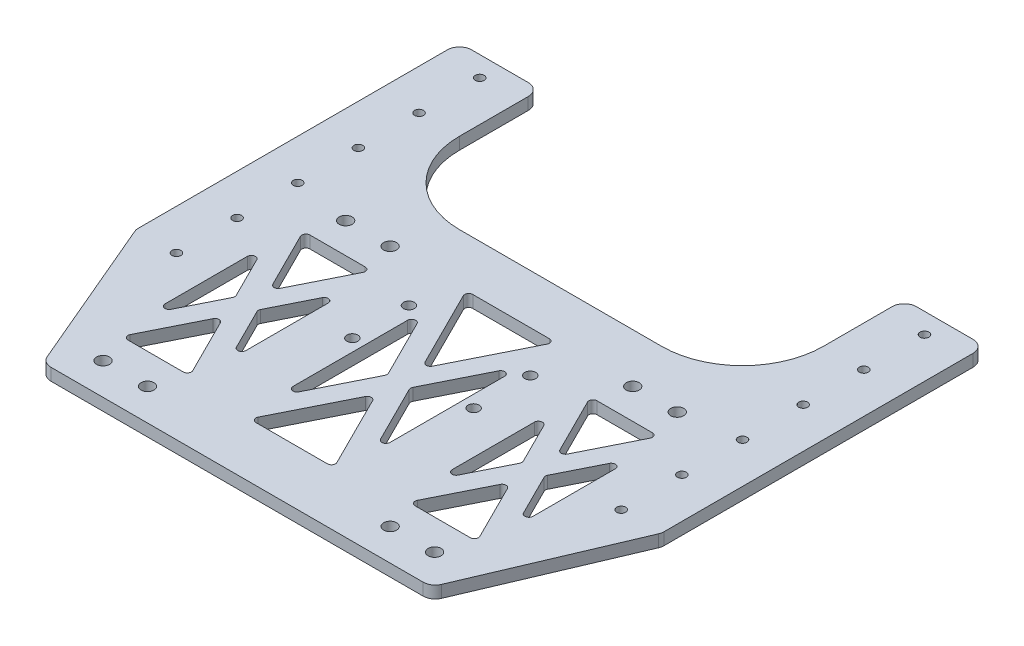
SolidWorks part; units mm, degrees
material "碳纤维"
ref_plane "前视基准面" through (0, 0, 0) normal (0, 0, 1) x (1, 0, 0)
ref_plane "上视基准面" through (0, 0, 0) normal (0, 1, 0) x (1, 0, 0)
ref_plane "右视基准面" through (0, 0, 0) normal (1, 0, 0) x (0, 0, -1)
sketch "草图1" plane through (0, 0, 0) normal (0, 1, 0) x (1, 0, 0)
  line L0 (20, 120) -> (20, 80)
  line L1 (0, 0) -> (130, 0)
  line L2 (0, 0) -> (0, 120)
  line L3 (0, 120) -> (20, 120)
  line L4 (130, 0) -> (130, 120)
  line L5 (65, 0) -> (65, 85) construction
  line L6 (20, 80) -> (110, 80)
  line L7 (110, 120) -> (110, 80)
  line L8 (110, 120) -> (130, 120)
  line L10 (50, 57.5) -> (50, 43.5) construction
  circle A0 centre (10, 115) radius 1.1
  circle A1 centre (120, 115) radius 1.1
  circle A2 centre (10, 100) radius 1.1
  circle A3 centre (120, 100) radius 1.1
  circle A4 centre (10, 85) radius 1.1
  circle A5 centre (120, 85) radius 1.1
  circle A6 centre (10, 70) radius 1.1
  circle A7 centre (120, 70) radius 1.1
  circle A8 centre (10, 55) radius 1.1
  circle A9 centre (120, 55) radius 1.1
  circle A10 centre (10, 40) radius 1.1
  circle A11 centre (120, 40) radius 1.1
  circle A12 centre (50, 57.5) radius 1.35
  circle A13 centre (50, 43.5) radius 1.35
  circle A14 centre (80, 43.5) radius 1.35
  circle A15 centre (80, 57.5) radius 1.35
  point P11 (65, 80)
  dimension "D5" = 2.2
  dimension "D6" = 5
  dimension "D8" = 15
  dimension "D9" = 43.5
  dimension "D10" = 14
  dimension "D11" = 2.7
  dimension "D12" = 30
  dimension "D13" = 10
  dimension "D1" = 130
  dimension "D2" = 120
  dimension "D3" = 40
  dimension "D4" = 90
  dimension "D7" = 6
extrude "凸台-拉伸1" add sketch "草图1" along normal blind 3
sketch "草图2" plane through (0, 0, 0) normal (0, -1, 0) x (1, 0, 0)
  line L0 (35, -7.85) -> (24, -7.85) construction
  line L1 (35, -67.85) -> (35, -7.85) construction
  line L2 (42, -37.85) -> (17, -37.85) construction
  line L3 (29.5, -7.85) -> (29.5, -37.85) construction
  line L4 (65, -80) -> (65, 0) construction
  line L5 (110, -80) -> (20, -80) construction
  line L6 (0, 0) -> (130, 0) construction
  line L8 (42, -12.85) -> (17, -12.85) construction
  line L9 (42, -12.85) -> (42, -62.85) construction
  line L10 (42, -62.85) -> (17, -62.85) construction
  line L11 (17, -12.85) -> (17, -62.85) construction
  line L15 (50.5, -40) -> (65, -40) construction
  line L16 (50.5, -11) -> (79.5, -11) construction
  line L17 (50.5, -11) -> (50.5, -69) construction
  line L18 (50.5, -69) -> (79.5, -69) construction
  line L19 (79.5, -11) -> (79.5, -69) construction
  line L20 (17, -12.85) -> (29.5, -37.85) construction
  line L21 (42, -12.85) -> (29.5, -37.85) construction
  line L22 (29.5, -12.85) -> (29.5, -7.85) construction
  line L23 (35, -48.85) -> (42, -62.85) construction
  line L24 (29.5, -37.85) -> (42, -62.85) construction
  line L25 (29.5, -37.85) -> (17, -62.85) construction
  line L26 (37.9549, -15.35) -> (29.5, -32.2598)
  line L27 (19.5, -23.4402) -> (26.7049, -37.85)
  line L28 (29.5, -43.4402) -> (21.0451, -60.35)
  line L29 (26.7049, -37.85) -> (19.5, -52.2598)
  line L30 (29.5, -43.4402) -> (37.9549, -60.35)
  line L31 (37.9549, -15.35) -> (21.0451, -15.35)
  line L32 (90.5, -23.4402) -> (97.7049, -37.85)
  line L33 (37.9549, -60.35) -> (21.0451, -60.35)
  line L34 (39.5, -23.4402) -> (39.5, -52.2598)
  line L35 (90.5, -23.4402) -> (90.5, -52.2598)
  line L36 (19.5, -23.4402) -> (19.5, -52.2598)
  line L37 (97.7049, -37.85) -> (90.5, -52.2598)
  line L38 (32.2951, -37.85) -> (39.5, -52.2598)
  line L39 (39.5, -23.4402) -> (32.2951, -37.85)
  line L40 (42, -60.35) -> (17, -60.35) construction
  line L41 (27.2639, -38.968) -> (39.7639, -63.968) construction
  line L42 (21.0451, -15.35) -> (29.5, -32.2598)
  line L43 (100.5, -43.4402) -> (92.0451, -60.35)
  line L44 (44.2361, -13.968) -> (31.7361, -38.968) construction
  line L45 (100.5, -43.4402) -> (108.9549, -60.35)
  line L46 (14.7639, -13.968) -> (27.2639, -38.968) construction
  line L47 (92.0451, -60.35) -> (108.9549, -60.35)
  line L48 (27.2639, -36.732) -> (14.7639, -61.732) construction
  line L49 (31.7361, -36.732) -> (44.2361, -61.732) construction
  line L50 (110.5, -23.4402) -> (103.2951, -37.85)
  line L51 (19.5, -12.85) -> (19.5, -62.85) construction
  line L52 (103.2951, -37.85) -> (110.5, -52.2598)
  line L53 (110.5, -23.4402) -> (110.5, -52.2598)
  line L54 (92.0451, -15.35) -> (108.9549, -15.35)
  line L55 (92.0451, -15.35) -> (100.5, -32.2598)
  line L56 (108.9549, -15.35) -> (100.5, -32.2598)
  line L57 (65, -11) -> (65, 0) construction
  line L58 (50.5, -11) -> (65, -40) construction
  line L59 (65, -40) -> (79.5, -69) construction
  line L60 (79.5, -11) -> (65, -40) construction
  line L61 (65, -40) -> (50.5, -69) construction
  line L62 (54.5451, -13.5) -> (75.4549, -13.5)
  line L63 (75.4549, -13.5) -> (65, -34.4098)
  line L64 (53, -21.5902) -> (62.2049, -40)
  line L65 (62.2049, -40) -> (53, -58.4098)
  line L67 (65, -45.5902) -> (76.0799, -67.75)
  line L69 (77, -21.5902) -> (77, -58.4098)
  line L70 (50.5, -13.5) -> (79.5, -13.5) construction
  line L71 (54.5451, -13.5) -> (65, -34.4098)
  line L72 (53, -21.5902) -> (53, -58.4098)
  line L74 (67.2361, -38.882) -> (81.7361, -67.882) construction
  line L75 (67.7951, -40) -> (77, -58.4098)
  line L76 (77, -21.5902) -> (67.7951, -40)
  line L77 (52.7361, -9.882) -> (67.2361, -38.882) construction
  line L78 (62.7639, -38.882) -> (48.2639, -67.882) construction
  line L79 (53.9201, -67.75) -> (76.0799, -67.75)
  line L80 (53, -11) -> (53, -69) construction
  line L82 (62.7639, -41.118) -> (77.2639, -70.118) construction
  line L83 (77, -11) -> (77, -69) construction
  line L84 (81.7361, -12.118) -> (67.2361, -41.118) construction
  line L85 (65, -45.5902) -> (53.9201, -67.75)
  circle A16 centre (24, -7.85) radius 1.6
  circle A17 centre (35, -7.85) radius 1.6
  circle A18 centre (35, -67.85) radius 1.6
  circle A19 centre (24, -67.85) radius 1.6
  circle A20 centre (95, -67.85) radius 1.6
  circle A21 centre (106, -67.85) radius 1.6
  circle A22 centre (95, -7.85) radius 1.6
  circle A23 centre (106, -7.85) radius 1.6
  point P18 (42, -37.85)
  point P20 (39.5, -11.35)
  point P21 (14.5, -11.35)
  point P49 (38.1584, -12.1792)
  point P51 (38, -12.85)
  point P52 (38, -62.85)
  point P55 (39.5, -14.35)
  point P56 (14.5, -14.35)
  point P57 (15.8416, -12.1792)
  point P62 (15.8416, -63.5208)
  point P63 (37.8053, -11.1971)
  point P69 (39.5, -64.35)
  point P70 (14.5, -64.35)
  point P79 (38.5, -10)
  point P93 (38.5, -65)
  point P96 (40, -67.5)
  point P97 (70, -67.5)
  point P100 (67.8053, -8.8029)
  point P104 (40, -7.5)
  point P105 (70, -7.5)
  point P111 (42.1947, -66.1971)
  point P112 (40, -63.5)
  point P113 (70, -63.5)
  dimension "D1" = 3.2
  dimension "D2" = 60
  dimension "D4" = 7.85
  dimension "D3" = 11
  dimension "D5" = 30
  dimension "D6" = 25
  dimension "D7" = 50
  dimension "D8" = 29
  dimension "D9" = 2.5
  dimension "D10" = 11
  dimension "D13" = 2.5
  dimension "D14" = 2.5
  dimension "D16" = 2.5
  dimension "D11" = 2.5
  dimension "D12" = 2.5
  dimension "D15" = 2.5
extrude "切除-拉伸1" cut sketch "草图2" against normal through all
sketch "草图3" plane through (0, 3, 0) normal (0, 1, 0) x (1, 0, 0)
  line L0 (17, 0) -> (0, 40)
  line L1 (0, 0) -> (130, 0) construction
  line L2 (0, 120) -> (0, 0) construction
  line L3 (65, 80) -> (65, 0) construction
  line L4 (110, 80) -> (20, 80) construction
  line L5 (113, 0) -> (130, 40)
  line L6 (0, 40) -> (0, 0)
  line L7 (0, 0) -> (17, 0)
  line L8 (130, 0) -> (113, 0)
  line L9 (130, 40) -> (130, 0)
  dimension "D1" = 17
  dimension "D2" = 40
extrude "切除-拉伸2" cut sketch "草图3" against normal through all
fillet "圆角1" radius 3 8 edges at (110, 1.5, -120) (130, 1.5, -120) (20, 1.5, -120) (0, 1.5, -120) (17, 1.5, 0) (113, 1.5, 0) (130, 1.5, -40) (0, 1.5, -40)
fillet "圆角2" radius 1 36 edges at (62.2049, 1.5, -40) (53, 1.5, -58.4098) (53, 1.5, -21.5902) (77, 1.5, -21.5902) (77, 1.5, -58.4098) (67.7951, 1.5, -40) (75.4549, 1.5, -13.5) (65, 1.5, -34.4098) (54.5451, 1.5, -13.5) (29.5, 1.5, -43.4402) (37.9549, 1.5, -60.35) (21.0451, 1.5, -60.35) (103.2951, 1.5, -37.85) (110.5, 1.5, -23.4402) (110.5, 1.5, -52.2598) (92.0451, 1.5, -60.35) (100.5, 1.5, -43.4402) (108.9549, 1.5, -60.35) (108.9549, 1.5, -15.35) (100.5, 1.5, -32.2598) (92.0451, 1.5, -15.35) (76.0799, 1.5, -67.75) (53.9201, 1.5, -67.75) (65, 1.5, -45.5902) (39.5, 1.5, -23.4402) (39.5, 1.5, -52.2598) (32.2951, 1.5, -37.85) (97.7049, 1.5, -37.85) (90.5, 1.5, -52.2598) (90.5, 1.5, -23.4402) (19.5, 1.5, -52.2598) (26.7049, 1.5, -37.85) (19.5, 1.5, -23.4402) (29.5, 1.5, -32.2598) (37.9549, 1.5, -15.35) (21.0451, 1.5, -15.35)
fillet "圆角3" radius 20 2 edges at (110, 1.5, -80) (20, 1.5, -80)
